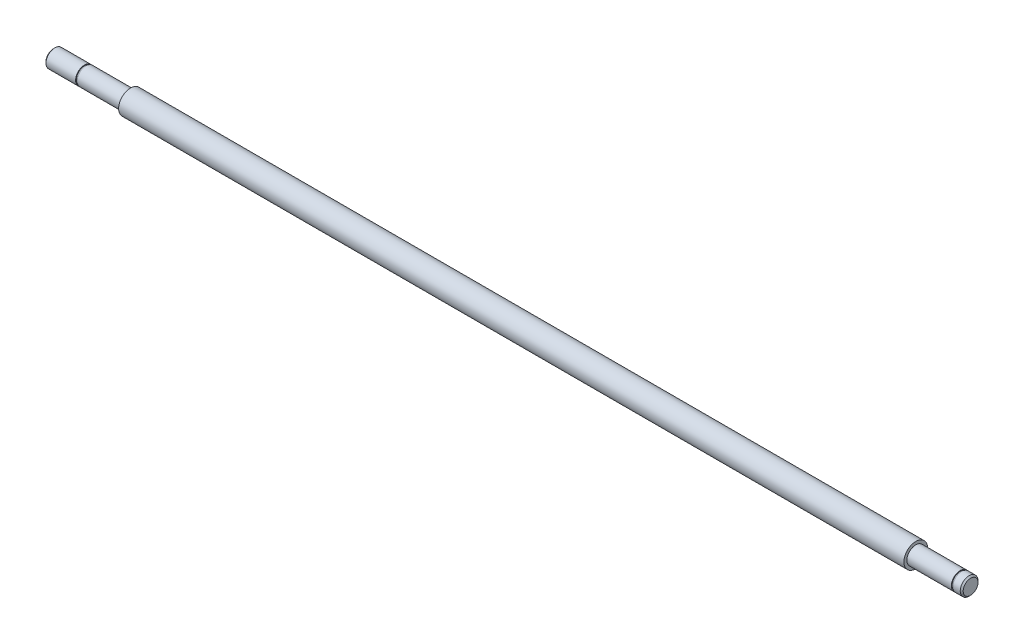
SolidWorks part; units mm, degrees
material "AISI 304"
ref_plane "前视基准面" through (0, 0, 0) normal (0, 0, 1) x (1, 0, 0)
ref_plane "上视基准面" through (0, 0, 0) normal (0, 1, 0) x (1, 0, 0)
ref_plane "右视基准面" through (0, 0, 0) normal (1, 0, 0) x (0, 0, -1)
sketch "草图1" plane through (0, 0, 0) normal (0, 0, 1) x (1, 0, 0)
  line L0 (0, 42.7939) -> (0, 0) construction
  line L1 (0, 0) -> (300.2071, 0) construction
  line L2 (-132.5, 4) -> (132.5, 4)
  line L3 (132.5, 4) -> (132.5, 3)
  line L4 (132.5, 3) -> (147.5, 3)
  line L5 (147.5, 3) -> (147.5, 2.75)
  line L6 (147.5, 2.75) -> (148, 2.75)
  line L7 (148, 2.75) -> (148, 3)
  line L8 (148, 3) -> (151, 3)
  line L9 (151, 3) -> (151, 0)
  line L10 (151, 0) -> (-158.5, 0)
  line L11 (-148, 2.75) -> (-148, 3)
  line L12 (-147.5, 2.75) -> (-148, 2.75)
  line L13 (-147.5, 3) -> (-147.5, 2.75)
  line L14 (-132.5, 3) -> (-147.5, 3)
  line L15 (-132.5, 4) -> (-132.5, 3)
  line L16 (-148, 3) -> (-158.5, 3)
  line L17 (-158.5, 3) -> (-158.5, 0)
  dimension "D1" = 265
  dimension "D2" = 8
  dimension "D3" = 6
  dimension "D4" = 15
  dimension "D5" = 3
  dimension "D6" = 0.5
  dimension "D7" = 5.5
  dimension "D8" = 11
revolve "旋转1" add sketch "草图1" angle 360 about L1
sketch "草图2" plane through (0, 0, 0) normal (0, 0, 1) x (1, 0, 0)
  line L0 (0, 0) -> (0, 18.8756) construction
  line L1 (132.5, 3) -> (133.5, 3)
  line L2 (132.5, 3) -> (132.5, 2.5)
  line L3 (132.5, 2.5) -> (133.5, 2.5)
  line L4 (133.5, 3) -> (133.5, 2.5)
  line L5 (-133.5, 3) -> (-133.5, 2.5)
  line L6 (-132.5, 2.5) -> (-133.5, 2.5)
  line L7 (-132.5, 3) -> (-132.5, 2.5)
  line L8 (-132.5, 3) -> (-133.5, 3)
  line L9 (0, 0) -> (286.9704, 0) construction
  dimension "D1" = 0.5
  dimension "D2" = 1
revolve "切除-旋转1" [suppressed] cut sketch "草图2" angle 360 about L9
chamfer "倒角1" distance 0.5 angle 45 2 edges at (151, 0, 3) (-158.5, 0, 3)
